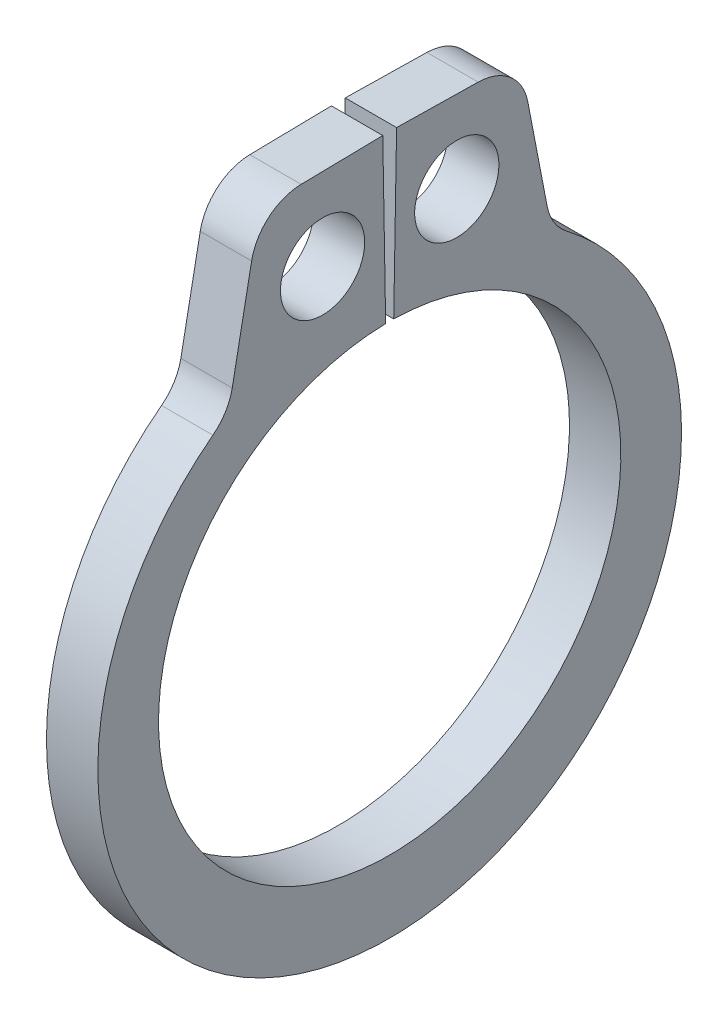
SolidWorks part; units mm, degrees
material "Cast Carbon Steel"
ref_plane "Front" through (0, 0, 0) normal (0, 0, 1) x (1, 0, 0)
ref_plane "Top" through (0, 0, 0) normal (0, 1, 0) x (1, 0, 0)
ref_plane "Right" through (0, 0, 0) normal (1, 0, 0) x (0, 0, -1)
sketch "Sketch1" plane through (0, 0, 0) normal (1, 0, 0) x (0, 0, -1)
  line L0 (0, 0) -> (0, 2.8575) construction
  line L1 (-0.0499, 2.8571) -> (-0.0853, 4.8888)
  line L2 (0.0853, 4.8888) -> (1.6091, 4.8622)
  line L3 (1.6091, 4.8622) -> (1.9944, 2.867)
  line L4 (0.0499, 2.8571) -> (0.0853, 4.8888)
  line L5 (-0.0853, 4.8888) -> (-1.6091, 4.8622)
  line L6 (-1.6091, 4.8622) -> (-1.9944, 2.867)
  line L7 (-1.9944, 2.867) -> (-1.6318, 2.3457) construction
  line L8 (1.9944, 2.867) -> (1.6318, 2.3457) construction
  line L9 (0, -2.8575) -> (0, -3.7465) construction
  line L10 (-1.6091, 4.8622) -> (-0.0499, 2.8571) construction
  line L11 (0, 2.8575) -> (0, 4.8895) construction
  line L12 (-2.8575, 0) -> (2.8575, 0) construction
  circle A0 centre (0, 0) radius 2.8575 construction
  arc A1 (-0.0499, 2.8571) -> (0.0499, 2.8571) centre (0, 0) ccw
  circle A3 centre (0, 0) radius 5.588 construction
  circle A4 centre (-0.8295, 3.8596) radius 0.5207
  circle A5 centre (0.8295, 3.8596) radius 0.5207
  arc A6 (-1.9944, 2.867) -> (1.9944, 2.867) centre (0, -0.139) ccw
  point P0 (0, -3.7465)
  dimension "A" = 5.715
  dimension "Hole" = 1.0414
  dimension "Smin" = 0.635
  dimension "H" = 2.032
  dimension "D2" = 1.524
  dimension "Angle" = 1
extrude "Extrude1" add sketch "Sketch1" along normal mid plane 0.635
fillet "Fillet1" radius 0.635 4 edges at (0, 2.867, 1.9944) (0, 2.867, -1.9944) (0, 4.8622, 1.6091) (0, 4.8622, -1.6091)
sketch "Sketch2" plane through (0, 0, 0) normal (0, 0, 1) x (1, 0, 0)
  line L0 (-3.5433, 0) -> (9.1567, 0)
  line L1 (9.1567, 0) -> (9.1567, -3.175)
  line L2 (-0.3683, -3.175) -> (-3.2893, -3.175)
  line L3 (9.1567, -3.175) -> (0.3683, -3.175)
  line L4 (0.3683, -3.175) -> (0.3683, -2.921)
  line L5 (0.3683, -2.921) -> (-0.3683, -2.921)
  line L6 (-0.3683, -2.921) -> (-0.3683, -3.175)
  line L7 (-0.3683, -3.175) -> (-3.5433, -3.175) construction
  line L8 (-3.5433, -3.175) -> (-3.5433, 0) construction
  line L9 (9.1567, 0) -> (76.391, 0) construction
  line L10 (-3.2893, -3.175) -> (-3.5433, -2.921)
  line L11 (-3.5433, -2.921) -> (-3.5433, 0)
  point P10 (0, -2.921)
  dimension "D2" = 12.7
  dimension "D3" = 3.175
  dimension "D1" = 45
revolve "Revolve1" [suppressed] add sketch "Sketch2" angle 360 about L9
delete or keep bodies "Body-Delete1" [suppressed] type delete bodies bodies 122
equation "\"D2@Sketch2\" = \"D1@Extrude1\"*20"
equation "\"D3@Sketch2\" = \"D2@Sketch2\"/4"
equation "\"D2@Sketch1\" = \"H@Sketch1\"*.75"
